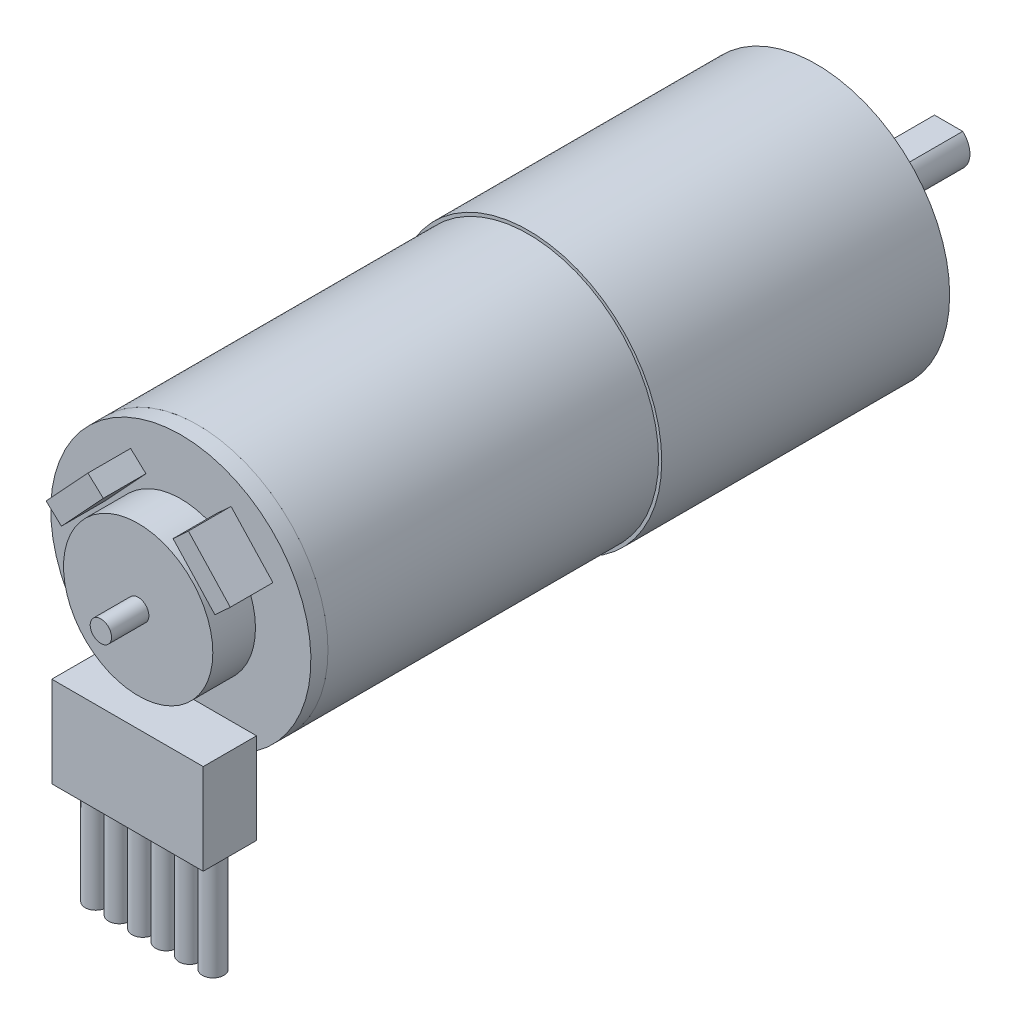
SolidWorks part; units mm, degrees
ref_plane "Plan de face" through (0, 0, 0) normal (0, 0, 1) x (1, 0, 0)
ref_plane "Plan de dessus" through (0, 0, 0) normal (0, 1, 0) x (1, 0, 0)
ref_plane "Plan de droite" through (0, 0, 0) normal (1, 0, 0) x (0, 0, -1)
sketch "Esquisse1" plane through (0, 0, 0) normal (0, 0, 1) x (1, 0, 0)
  circle A0 centre (0, 0) radius 12.5
  dimension "D1" = 25
extrude "Boss.-Extru.1" add sketch "Esquisse1" along normal blind 27
sketch "Esquisse5" plane through (0, 0, 0) normal (0, 0, -1) x (-1, 0, 0)
  circle A0 centre (0, 0) radius 3.5
  dimension "D1" = 7
extrude "Boss.-Extru.5" add sketch "Esquisse5" along normal blind 2.7
sketch "Esquisse6" plane through (0, 0, -2.7) normal (0, 0, -1) x (-1, 0, 0)
  circle A0 centre (0, 0) radius 2
  dimension "D1" = 4
extrude "Boss.-Extru.6" add sketch "Esquisse6" along normal blind 9.7
sketch "Esquisse7" plane through (0, 0, -12.4) normal (0, 0, -1) x (-1, 0, 0)
  line L1 (-1.3229, 2.6892) -> (1.3229, 2.6892)
  line L2 (-1.3229, 2.6892) -> (-1.3229, 1.5)
  line L3 (-1.3229, 1.5) -> (1.3229, 1.5)
  line L4 (1.3229, 2.6892) -> (1.3229, 1.5)
  circle A0 centre (0, 0) radius 2 construction
  circle A1 centre (0, 0) radius 2 construction
  dimension "D1" = 1.5
extrude "Enlèv. mat.-Extru.1" cut sketch "Esquisse7" against normal blind 8
hole_wizard "Dégagement M31" positions "Esquisse8" profile "Esquisse10" hole size "M3" standard "ISO"
sketch "Esquisse8" plane through (0, 0, 0) normal (0, 0, -1) x (-1, 0, 0)
  line L0 (0, 0) -> (-5.4601, 0) construction
  point P0 (0, 8.5)
  point P8 (0, -8.5)
  dimension "D1" = 17
sketch "Esquisse10" plane through (0, 8.5, 0) normal (1, 0, 0) x (0, 1, 0)
  line L0 (0, 0) -> (0, 7.0215)
  line L1 (0, 7.0215) -> (1.7, 6)
  line L2 (1.7, 6) -> (1.7, 0)
  line L5 (1.7, 0) -> (0, 0)
  line L10 (0, 7.0215) -> (-1.7, 6) construction
  line L11 (0, -6.35) -> (0, 107.95) construction
  dimension "Diamètre du perçage" = 3.4
  dimension "Profondeur du perçage" = 6
  dimension "Angle de pointe" = 118
sketch "Esquisse2" plane through (0, 0, 27) normal (0, 0, 1) x (1, 0, 0)
  circle A0 centre (0, 0) radius 12.2
  dimension "D1" = 24.4
extrude "Boss.-Extru.2" add sketch "Esquisse2" along normal blind 31
sketch "Esquisse3" plane through (0, 0, 58) normal (0, 0, 1) x (1, 0, 0)
  circle A1 centre (0, 0) radius 12.2
  circle A2 centre (0, 0) radius 12.2
  dimension "D1" = 0
extrude "Boss.-Extru.3" add sketch "Esquisse3" along normal blind 1.6 separate body
sketch "Esquisse4" plane through (0, 0, 59.6) normal (0, 0, 1) x (1, 0, 0)
  circle A0 centre (0, 0) radius 7
  dimension "D1" = 14
extrude "Boss.-Extru.4" add sketch "Esquisse4" along normal blind 4
sketch "Esquisse14" plane through (0, 0, 63.6) normal (0, 0, 1) x (1, 0, 0)
  circle A0 centre (0, 0) radius 1
  dimension "D1" = 2
extrude "Boss.-Extru.10" add sketch "Esquisse14" along normal blind 3.5
sketch "Esquisse12" plane through (0, 0, 59.6) normal (0, 0, 1) x (1, 0, 0)
  line L0 (-8.6375, 4.509) -> (-4.7094, 8.7362)
  line L1 (-4.7094, 8.7362) -> (-3.2724, 7.401)
  line L2 (-3.2724, 7.401) -> (-7.2006, 3.1737)
  line L3 (-7.2006, 3.1737) -> (-8.6375, 4.509)
  line L4 (0, 0) -> (0, 3.9458) construction
  line L5 (7.2006, 3.1737) -> (8.6375, 4.509)
  line L6 (3.2724, 7.401) -> (7.2006, 3.1737)
  line L7 (4.7094, 8.7362) -> (3.2724, 7.401)
  line L8 (8.6375, 4.509) -> (4.7094, 8.7362)
extrude "Boss.-Extru.8" add sketch "Esquisse12" along normal blind 4
sketch "Esquisse11" plane through (0, 0, 59.6) normal (0, 0, 1) x (1, 0, 0)
  line L1 (-7.1, -8.7) -> (7.1, -8.7)
  line L2 (-7.1, -8.7) -> (-7.1, -17.2)
  line L3 (-7.1, -17.2) -> (7.1, -17.2)
  line L4 (7.1, -8.7) -> (7.1, -17.2)
  point P4 (0, -8.7)
  dimension "D1" = 8.5
  dimension "D2" = 14.2
  dimension "D3" = 8.7
extrude "Boss.-Extru.7" add sketch "Esquisse11" along normal blind 5
sketch "Esquisse13" plane through (0, -17.2, 0) normal (0, -1, 0) x (1, 0, 0)
  line L0 (-7.1, 64.6) -> (-7.1, 59.6) construction
  circle A0 centre (-5.4747, 62.1) radius 1
  circle A1 centre (-3.2747, 62.1) radius 1
  circle A2 centre (-1.0747, 62.1) radius 1
  circle A3 centre (1.1253, 62.1) radius 1
  circle A4 centre (3.3253, 62.1) radius 1
  circle A5 centre (5.5253, 62.1) radius 1
  point P5 (-7.1, 62.1)
  dimension "D1" = 2
  dimension "D2" = 6
extrude "Boss.-Extru.9" add sketch "Esquisse13" along normal blind 10 contours A0
